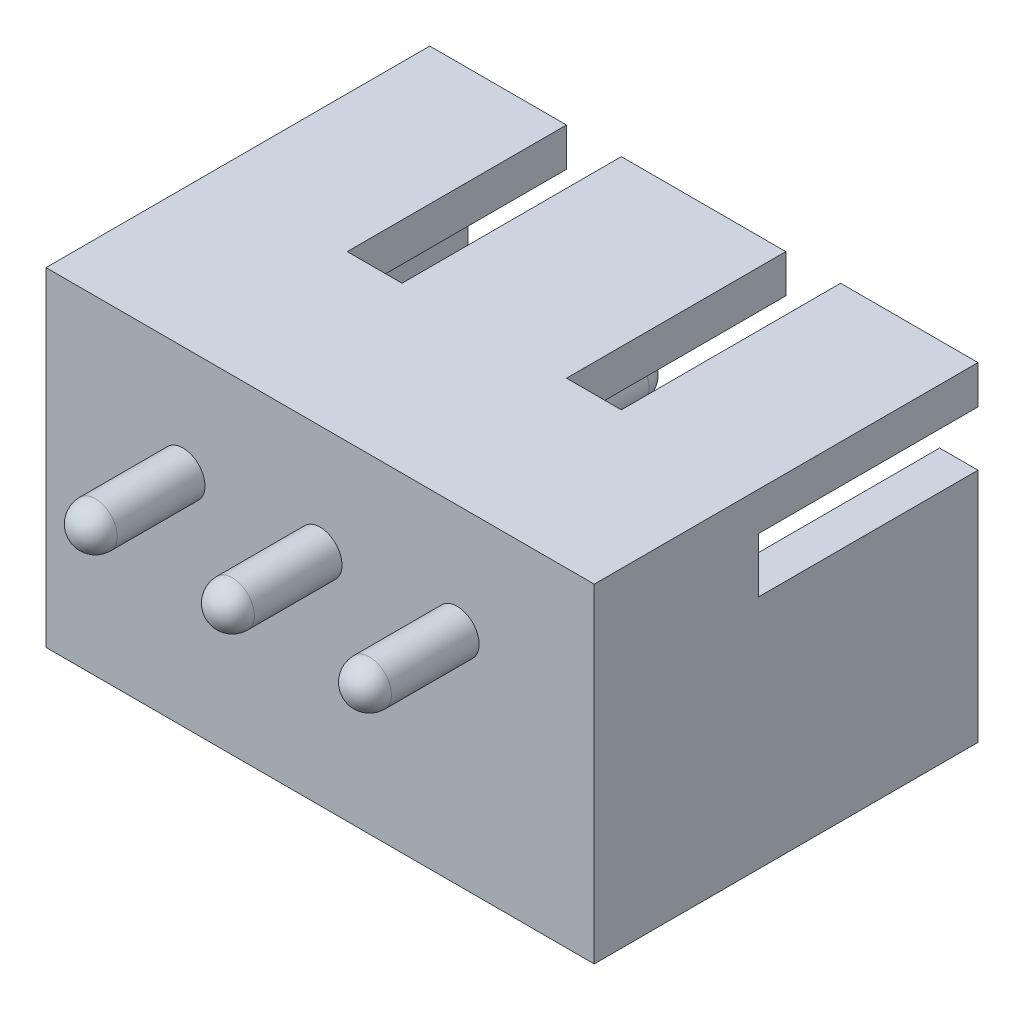
SolidWorks part; units mm, degrees
ref_plane "前视基准面" through (0, 0, 0) normal (0, 0, 1) x (1, 0, 0)
ref_plane "上视基准面" through (0, 0, 0) normal (0, 1, 0) x (1, 0, 0)
ref_plane "右视基准面" through (0, 0, 0) normal (1, 0, 0) x (0, 0, -1)
sketch "草图1" plane through (0, 0, 0) normal (0, 0, 1) x (1, 0, 0)
  line L1 (0, 0) -> (10, 0)
  line L2 (0, 0) -> (0, 6)
  line L3 (0, 6) -> (10, 6)
  line L4 (10, 0) -> (10, 6)
  dimension "D1" = 10
  dimension "D2" = 6
extrude "凸台-拉伸1" add sketch "草图1" along normal blind 7
sketch "草图2" plane through (0, 0, 0) normal (0, 0, 1) x (1, 0, 0)
  line L0 (0.7, 5.3) -> (9.3, 5.3)
  line L1 (9.3, 5.3) -> (9.3, 0.7)
  line L2 (9.3, 0.7) -> (0.7, 0.7)
  line L3 (0.7, 0.7) -> (0.7, 5.3)
  line L4 (0, 6) -> (0, 0) construction
  line L5 (10, 6) -> (0, 6) construction
  line L6 (10, 0) -> (10, 6) construction
  line L7 (0, 0) -> (10, 0) construction
  dimension "D1" = 0.7
  dimension "D2" = 0.7
  dimension "D3" = 0.7
  dimension "D4" = 0.7
extrude "切除-拉伸1" cut sketch "草图2" along normal blind 5
sketch "草图3" plane through (0, 6, 0) normal (0, 1, 0) x (1, 0, 0)
  line L0 (4.9941, 0.4894) -> (4.9941, -8.0713) construction
  line L1 (6.4941, 0) -> (6.4941, -4)
  line L2 (10, 0) -> (0, 0) construction
  line L3 (10, -7) -> (0, -7) construction
  line L4 (6.4941, 0) -> (7.4941, 0)
  line L5 (7.4941, 0) -> (7.4941, -4)
  line L6 (7.4941, -4) -> (6.4941, -4)
  line L7 (3.4941, 0) -> (2.4941, 0)
  line L8 (2.4941, -4) -> (3.4941, -4)
  line L9 (2.4941, 0) -> (2.4941, -4)
  line L10 (3.4941, 0) -> (3.4941, -4)
  dimension "D1" = 3
  dimension "D2" = 3
  dimension "D3" = 1
extrude "切除-拉伸2" cut sketch "草图3" against normal up to next
sketch "草图4" plane through (10, 0, 0) normal (1, 0, 0) x (0, 0, -1)
  line L0 (0, 5.3) -> (-4, 5.3)
  line L1 (0, 0) -> (0, 6) construction
  line L2 (-4, 5.3) -> (-4, 4.3)
  line L3 (-7, 0) -> (-7, 6) construction
  line L4 (-7, 6) -> (0, 6) construction
  line L5 (0, 4.3) -> (-4, 4.3)
  line L6 (0, 5.3) -> (0, 4.3)
  dimension "D1" = 3
  dimension "D2" = 0.7
  dimension "D3" = 1
extrude "切除-拉伸3" cut sketch "草图4" against normal through all
sketch "草图5" plane through (0, 0, 5) normal (0, 0, -1) x (-1, 0, 0)
  line L0 (0.3372, 4) -> (-11.9383, 4) construction
  line L1 (-10, 6) -> (-7.4941, 6) construction
  line L2 (-5, -0.3505) -> (-5, 6.9681) construction
  line L3 (-10, 0) -> (-10, 4.3) construction
  circle A0 centre (-5, 4) radius 0.4
  circle A1 centre (-7.5, 4) radius 0.4
  circle A2 centre (-2.5, 4) radius 0.4
  dimension "D2" = 0.8
  dimension "D3" = 0.8
  dimension "D4" = 5
  dimension "D1" = 2
  dimension "D5" = 5
extrude "凸台-拉伸2" add sketch "草图5" along normal blind 4 and the other way blind 4
fillet "圆角1" radius 0.4 6 edges at (7.1, 4, 1) (4.6, 4, 1) (2.9, 4, 1) (7.1, 4, 9) (4.6, 4, 9) (2.9, 4, 9)
